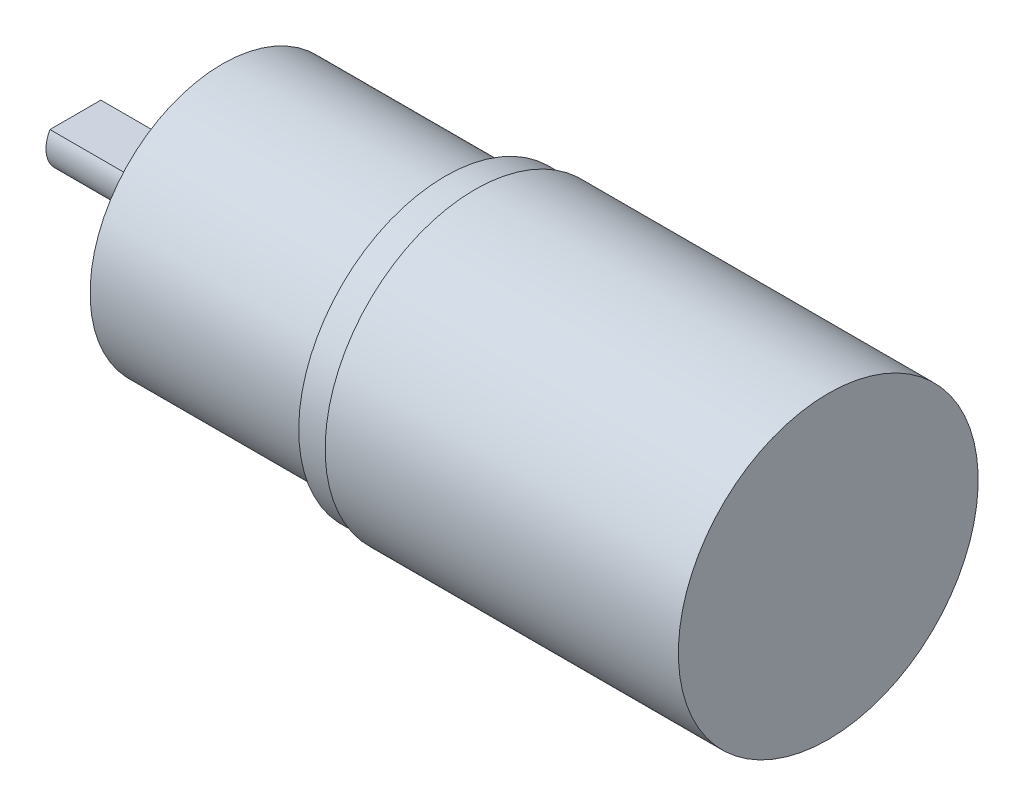
SolidWorks part; units mm, degrees
ref_plane "Piano frontale" through (0, 0, 0) normal (0, 0, 1) x (1, 0, 0)
ref_plane "Piano superiore" through (0, 0, 0) normal (0, 1, 0) x (1, 0, 0)
ref_plane "Piano destro" through (0, 0, 0) normal (1, 0, 0) x (0, 0, -1)
sketch "Schizzo1" plane through (0, 0, 0) normal (0, 0, 1) x (1, 0, 0)
  line L0 (15.2822, 23.8309) -> (-32.7753, 23.8309)
  line L1 (15.2822, 23.8309) -> (15.2822, 3.4348)
  line L2 (-32.7753, 23.8309) -> (-32.7753, 23.3503)
  line L3 (-32.7753, 23.3503) -> (-36.8533, 23.3503)
  line L4 (-36.8533, 23.3503) -> (-36.8533, 21.4348)
  line L5 (-36.8533, 21.4348) -> (-67.1529, 21.4348)
  line L6 (-67.1529, 21.4348) -> (-67.1529, 14.4348)
  line L7 (-67.1529, 14.4348) -> (-68.9179, 14.4348)
  line L8 (-68.9179, 14.4348) -> (-68.9179, 9.2737)
  line L9 (-68.9179, 9.2737) -> (-69.6841, 9.2737)
  line L10 (-69.6841, 9.2737) -> (-69.6841, 7.4348)
  line L11 (-69.6841, 7.4348) -> (-87.1529, 7.4348)
  line L12 (-87.1529, 7.4348) -> (-87.1529, 3.4348)
  line L13 (15.2822, 3.4348) -> (-116.0352, 3.4348) construction
  line L14 (15.2822, 3.4348) -> (-87.1529, 3.4348)
  dimension "D1" = 11
  dimension "D2" = 18
  dimension "D3" = 4
  dimension "D4" = 20
revolve "Rivoluzione1" add sketch "Schizzo1" angle 360 about L13
sketch "Schizzo2" plane through (-67.1529, 0, 0) normal (-1, 0, 0) x (0, 0, 1)
  line L0 (0, 3.4348) -> (18.7776, 22.2124) construction
  line L1 (0, 3.4348) -> (26.9625, 3.4348) construction
  line L2 (0, 3.4348) -> (-19.1829, 22.6178) construction
  circle A0 centre (0, 3.4348) radius 14.0226 construction
  point P5 (9.9155, 13.3503)
  point P9 (-9.9155, 13.3503)
  point P11 (-9.9155, -6.4807)
  point P12 (9.9155, -6.4807)
  dimension "D1" = 45
hole_wizard "Foro Ø3.0 (3)-2" positions "Schizzo5" profile "Schizzo4" hole size "Ø3.0" standard "ISO"
sketch "Schizzo5" plane through (-67.1529, 0, 0) normal (-1, 0, 0) x (0, 0, 1)
  point P0 (-9.9155, 13.3503)
  point P3 (9.9155, 13.3503)
  point P6 (9.9155, -6.4807)
  point P9 (-9.9155, -6.4807)
sketch "Schizzo4" plane through (-67.1529, 13.3503, -9.9155) normal (0, 1, 0) x (0, 0, 1)
  line L0 (0, 0) -> (0, 8.9013)
  line L1 (0, 8.9013) -> (1.5, 8)
  line L2 (1.5, 8) -> (1.5, 0)
  line L5 (1.5, 0) -> (0, 0)
  line L10 (0, 8.9013) -> (-1.5, 8) construction
  line L11 (0, -6.35) -> (0, 107.95) construction
  dimension "Hole Dia." = 3
  dimension "Hole Depth" = 8
  dimension "Drill Angle" = 118
sketch "Schizzo6" plane through (-87.1529, 0, 0) normal (-1, 0, 0) x (0, 0, 1)
  line L0 (-6.9108, 5.4348) -> (7.7548, 5.4348)
  line L1 (-6.9108, 5.4348) -> (-6.9108, 7.7817)
  line L2 (-6.9108, 7.7817) -> (7.7548, 7.7817)
  line L3 (7.7548, 7.7817) -> (7.7548, 5.4348)
  circle A0 centre (0, 3.4348) radius 4 construction
  dimension "D1" = 2
extrude "Taglio-Estrusione1" cut sketch "Schizzo6" against normal blind 15
